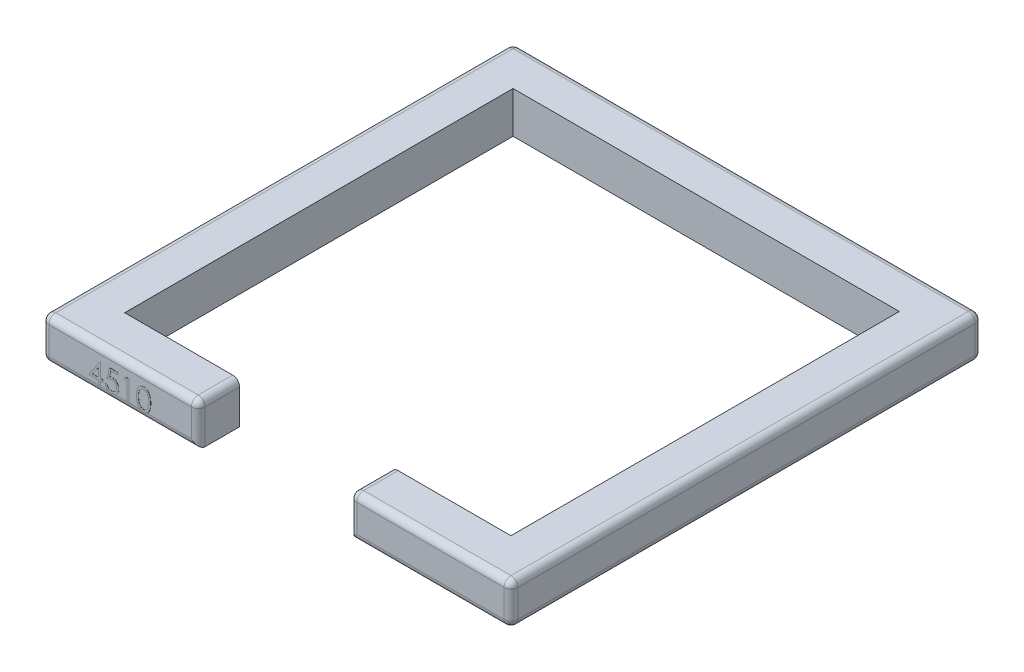
SolidWorks part; units mm, degrees
ref_plane "Front Plane" through (0, 0, 0) normal (0, 0, 1) x (1, 0, 0)
ref_plane "Top Plane" through (0, 0, 0) normal (0, 1, 0) x (1, 0, 0)
ref_plane "Right Plane" through (0, 0, 0) normal (1, 0, 0) x (0, 0, -1)
sketch "Sketch2" plane through (0, 0, 0) normal (0, 1, 0) x (1, 0, 0)
  line L0 (355.6, -357.5685) -> (-355.6, -357.5685)
  line L1 (-355.6, -357.5685) -> (-355.6, 357.5685)
  line L2 (-355.6, 357.5685) -> (355.6, 357.5685)
  line L3 (355.6, 357.5685) -> (355.6, -357.5685)
  line L4 (0, -357.5685) -> (0, 357.5685) construction
  line L5 (431.8, -433.7685) -> (-431.8, -433.7685)
  line L10 (431.8, -433.7685) -> (431.8, 433.7685)
  line L11 (431.8, 433.7685) -> (-431.8, 433.7685)
  line L12 (-431.8, -433.7685) -> (-431.8, 433.7685)
  line L13 (-355.6, 0) -> (355.6, 0) construction
  point P12 (0, 0)
  point P15 (0, 0)
  dimension "D1" = 711.2
  dimension "D2" = 715.137
  dimension "D3" = 76.2
  dimension "D4" = 76.2
  dimension "D5" = 76.2
  dimension "D6" = 76.2
extrude "Boss-Extrude1" add sketch "Sketch2" against normal blind 76.2
sketch "Sketch4" plane through (0, 0, 0) normal (0, 1, 0) x (1, 0, 0)
  line L0 (0, 0) -> (0, -357.5685) construction
  line L1 (-355.6, -357.5685) -> (355.6, -357.5685) construction
  line L2 (-144.0785, -357.5685) -> (135.3215, -357.5685)
  line L7 (-144.0785, -357.5685) -> (-144.0785, -433.7685)
  line L8 (-431.8, -433.7685) -> (431.8, -433.7685) construction
  line L9 (135.3215, -357.5685) -> (135.3215, -433.7685)
  line L10 (135.3215, -433.7685) -> (-144.0785, -433.7685)
  point P8 (-4.3785, -357.5685)
  dimension "D1" = 279.4
extrude "Cut-Extrude1" cut sketch "Sketch4" against normal through all
fillet "Fillet1" radius 12.7 18 edges at (-431.8, 0, 0) (283.5607, -76.2, 433.7685) (-287.9393, -76.2, 433.7685) (431.8, -38.1, 433.7685) (283.5607, 0, 433.7685) (-287.9393, 0, 433.7685) (-431.8, -38.1, 433.7685) (-431.8, -76.2, 0) (431.8, -76.2, 0) (0, -76.2, -433.7685) (431.8, -38.1, -433.7685) (-431.8, -38.1, -433.7685) (0, 0, -433.7685) (431.8, 0, 0) (135.3215, -38.1, 433.7685) (-144.0785, -38.1, 433.7685) (-144.0785, 0, 395.6685) (135.3215, 0, 395.6685)
sketch "Sketch5" plane through (0, 0, 433.7685) normal (0, 0, 1) x (1, 0, 0)
  text T0 "4510" font "Century Gothic" height 38.1
extrude "Boss-Extrude2" add sketch "Sketch5" along normal blind 0.254
